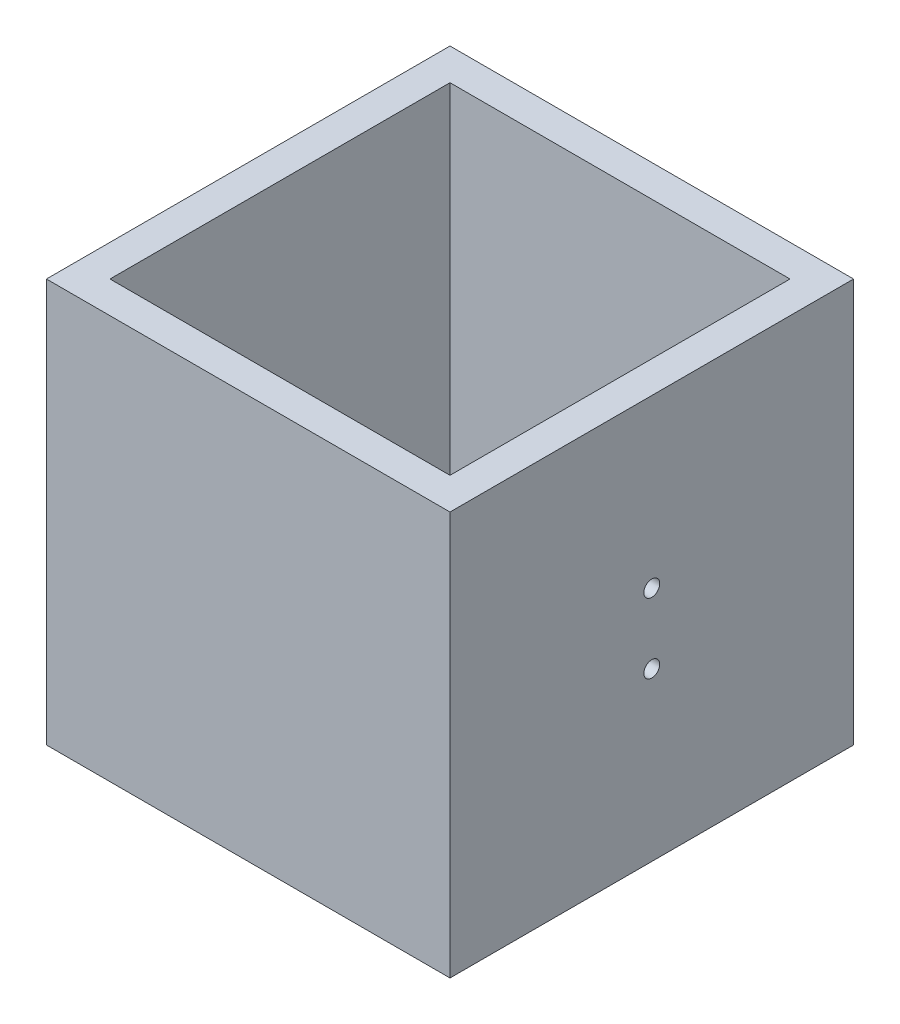
SolidWorks part; units mm, degrees
ref_plane "Front Plane" through (0, 0, 0) normal (0, 0, 1) x (1, 0, 0)
ref_plane "Top Plane" through (0, 0, 0) normal (0, 1, 0) x (1, 0, 0)
ref_plane "Right Plane" through (0, 0, 0) normal (1, 0, 0) x (0, 0, -1)
sketch "Sketch1" plane through (0, 0, 0) normal (0, 1, 0) x (1, 0, 0)
  line L1 (-12.7, -12.7) -> (12.7, -12.7)
  line L2 (-12.7, -12.7) -> (-12.7, 12.7)
  line L3 (-12.7, 12.7) -> (12.7, 12.7)
  line L4 (12.7, -12.7) -> (12.7, 12.7)
  line L5 (-12.7, -12.7) -> (12.7, 12.7) construction
  line L6 (-12.7, 12.7) -> (12.7, -12.7) construction
  point P0 (0, 0)
  dimension "D1" = 25.4
  dimension "D2" = 25.4
extrude "Boss-Extrude1" add sketch "Sketch1" along normal blind 25.4
shell "Shell1" thickness 2
sketch "Sketch2" plane through (12.7, 0, 0) normal (1, 0, 0) x (0, 0, -1)
  line L0 (-12.7, 0) -> (12.7, 0) construction
  circle A0 centre (0, 10.5) radius 0.5
  dimension "D1" = 1
  dimension "D2" = 10.5
extrude "Cut-Extrude1" cut sketch "Sketch2" against normal blind 6.4 contours A0
sketch "Sketch3" plane through (12.7, 0, 0) normal (1, 0, 0) x (0, 0, -1)
  line L0 (-12.7, 25.4) -> (12.7, 25.4) construction
  circle A0 centre (0, 14.9) radius 0.5
  point P2 (0, 0)
  dimension "D1" = 1
  dimension "D2" = 10.5
extrude "Cut-Extrude2" cut sketch "Sketch3" against normal blind 6.4
sketch "Sketch5" plane through (-12.7, 0, 0) normal (-1, 0, 0) x (0, 0, 1)
  line L0 (-12.7, 25.4) -> (12.7, 25.4) construction
  line L1 (-12, 24.7) -> (12, 24.7)
  line L2 (-12, 24.7) -> (-12, 0.7)
  line L3 (-12, 0.7) -> (12, 0.7)
  line L4 (12, 24.7) -> (12, 0.7)
  line L6 (12.7, 25.4) -> (12.7, 0) construction
  dimension "D1" = 24
  dimension "D2" = 24
  dimension "D3" = 0.7
  dimension "D4" = 0.7
extrude "Cut-Extrude3" cut sketch "Sketch5" against normal blind 1.5 contours L2 L3 L4 L1
